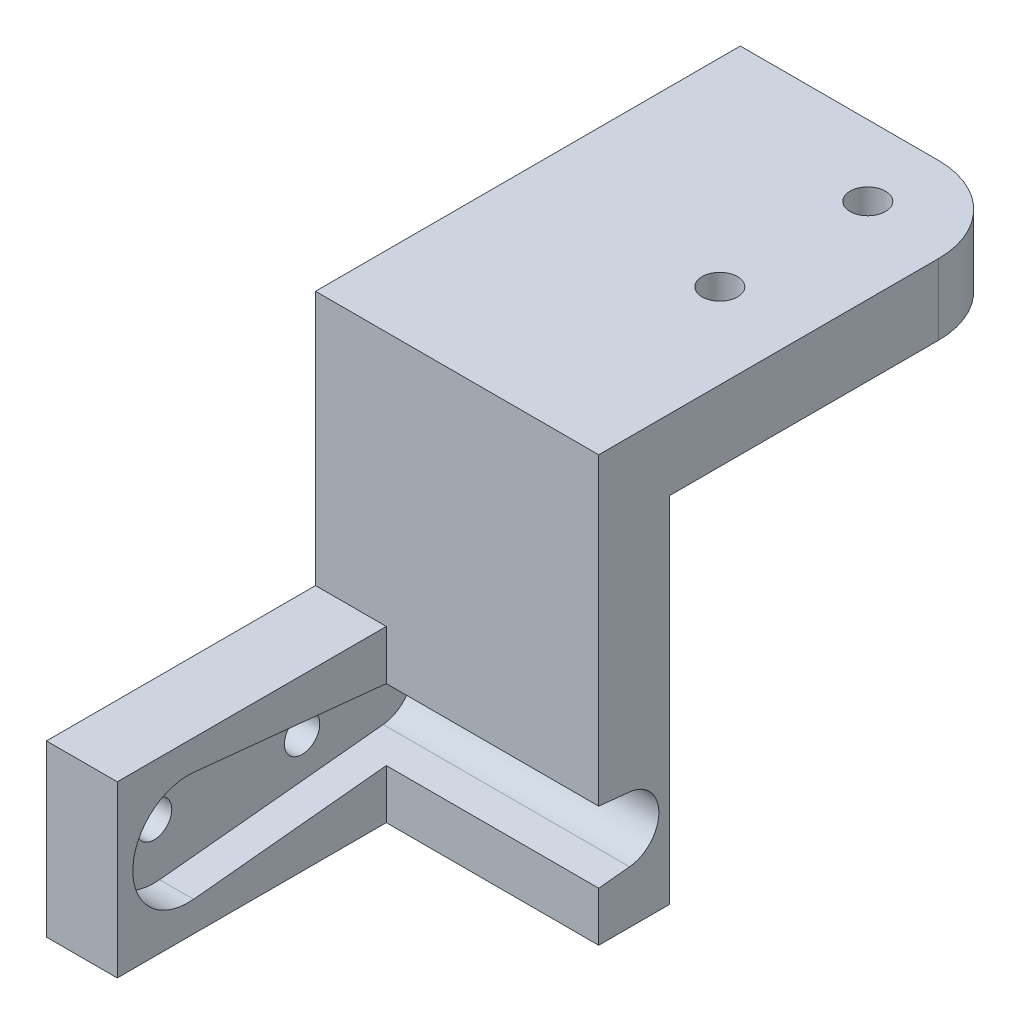
SolidWorks part; units mm, degrees
ref_plane "Front Plane" through (0, 0, 0) normal (0, 0, 1) x (1, 0, 0)
ref_plane "Top Plane" through (0, 0, 0) normal (0, 1, 0) x (1, 0, 0)
ref_plane "Right Plane" through (0, 0, 0) normal (1, 0, 0) x (0, 0, -1)
sketch "Sketch1" plane through (0, 0, 0) normal (0, 1, 0) x (1, 0, 0)
  line L1 (-10, 15) -> (10, 15)
  line L2 (-10, 15) -> (-10, -15)
  line L3 (-10, -15) -> (10, -15)
  line L4 (10, 15) -> (10, -15)
  line L5 (-10, 15) -> (10, -15) construction
  line L6 (-10, -15) -> (10, 15) construction
  point P0 (0, 0)
  dimension "D1" = 20
  dimension "D2" = 30
extrude "Boss-Extrude1" add sketch "Sketch1" along normal blind 5
sketch "Sketch2" plane through (0, 0, 0) normal (0, -1, 0) x (1, 0, 0)
  line L0 (7.4823, -9.6489) -> (5.8904, 6.1406) construction
  line L1 (0.5177, -9.6489) -> (2.1096, 6.1406) construction
  line L2 (10, -15) -> (-10, -15) construction
  line L3 (10, 15) -> (10, -15) construction
  line L4 (0.1197, -9.6088) -> (1.7116, 6.1807)
  line L5 (7.8803, -9.6088) -> (6.2884, 6.1807)
  arc A0 (0.5177, -9.6489) -> (7.4823, -9.6489) centre (4, -10) ccw construction
  arc A1 (5.8904, 6.1406) -> (2.1096, 6.1406) centre (4, 5.95) ccw construction
  arc A2 (6.2884, 6.1807) -> (1.7116, 6.1807) centre (4, 5.95) ccw
  arc A3 (0.1197, -9.6088) -> (7.8803, -9.6088) centre (4, -10) ccw
  dimension "D1" = 7
  dimension "D3" = 3.8
  dimension "D2" = 15.95
  dimension "D4" = 5
  dimension "D5" = 6
  dimension "D6" = 0.4
extrude "Cut-Extrude1" cut sketch "Sketch2" against normal blind 2.4
sketch "Sketch7" plane through (0, 2.4, 0) normal (0, -1, 0) x (1, 0, 0)
  circle A0 centre (4, -10) radius 1.25
  circle A1 centre (4, 0.45) radius 1.25
  dimension "D1" = 2.5
  dimension "D3" = 2.5
  dimension "D2" = 10.45
extrude "Cut-Extrude4" cut sketch "Sketch7" against normal through all
sketch "Sketch4" plane through (0, 0, 0) normal (1, 0, 0) x (0, 0, -1)
  line L0 (-15, 0) -> (15, 0) construction
  line L1 (-15, 0) -> (-10, 0)
  line L2 (-15, 0) -> (-15, -13)
  line L3 (-15, -25) -> (-10, -25)
  line L4 (-10, 0) -> (-10, -25)
  line L6 (-15, -13) -> (-34, -13)
  line L8 (-15, -25) -> (-34, -25)
  line L9 (-34, -13) -> (-34, -25)
  dimension "D1" = 25
  dimension "D2" = 5
  dimension "D3" = 13
  dimension "D4" = 24
extrude "Boss-Extrude2" add sketch "Sketch4" along normal mid plane 20
sketch "Sketch5" plane through (10, 0, 0) normal (1, 0, 0) x (0, 0, -1)
  line L1 (-34, -25) -> (-15, -25)
  line L2 (-34, -25) -> (-34, -13)
  line L3 (-34, -13) -> (-15, -13)
  line L4 (-15, -25) -> (-15, -13)
extrude "Cut-Extrude2" cut sketch "Sketch5" against normal offset from surface (15 mm away) 5 up to face at (-10, -8.25, 11)
sketch "Sketch6" plane through (-5, 0, 0) normal (1, 0, 0) x (0, 0, -1)
  line L0 (-28.6489, -15.5177) -> (-12.8594, -17.1096) construction
  line L1 (-28.6489, -22.4823) -> (-12.8594, -20.8904) construction
  line L2 (-34, -25) -> (-34, -13) construction
  line L3 (-28.6088, -22.8803) -> (-12.8193, -21.2884)
  line L4 (-28.6088, -15.1197) -> (-12.8193, -16.7116)
  arc A0 (-28.6489, -15.5177) -> (-28.6489, -22.4823) centre (-29, -19) ccw construction
  arc A1 (-12.8594, -20.8904) -> (-12.8594, -17.1096) centre (-13.05, -19) ccw construction
  arc A2 (-28.6088, -15.1197) -> (-28.6088, -22.8803) centre (-29, -19) ccw
  arc A3 (-12.8193, -21.2884) -> (-12.8193, -16.7116) centre (-13.05, -19) ccw
  point P12 (-34, -19)
  dimension "D1" = 7
  dimension "D2" = 3.8
  dimension "D3" = 15.95
  dimension "D4" = 5
  dimension "D5" = 0.4
extrude "Cut-Extrude3" cut sketch "Sketch6" against normal blind 2.4 and the other way through all
sketch "Sketch8" plane through (-7.4, 0, 0) normal (1, 0, 0) x (0, 0, -1)
  circle A0 centre (-29, -19) radius 1.25
  arc A1 (-28.6088, -15.1197) -> (-28.6088, -22.8803) centre (-29, -19) ccw construction
  circle A2 centre (-18.55, -19) radius 1.25
  dimension "D1" = 2.5
  dimension "D2" = 10.45
extrude "Cut-Extrude5" cut sketch "Sketch8" against normal through all
fillet "Fillet1" radius 6 1 edges at (10, 2.5, -15)
mirror "Mirror1" [suppressed]
delete or keep bodies "Body-Delete/Keep 1" [suppressed] type delete bodies bodies 107
mirror "Mirror2" [suppressed]
delete or keep bodies "Body-Delete/Keep 2" [suppressed] type delete bodies bodies 107
mirror "Mirror3" [suppressed]
delete or keep bodies "Body-Delete/Keep 3" [suppressed] type delete bodies bodies 111
